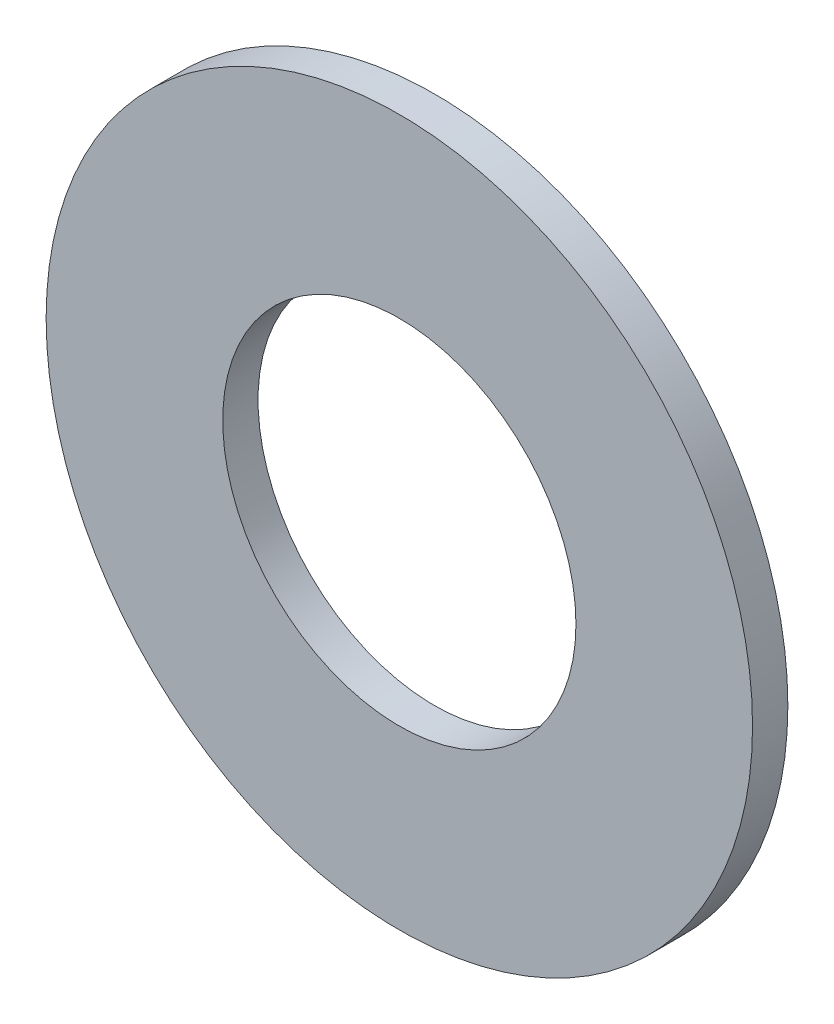
SolidWorks part; units mm, degrees
ref_plane "前视基准面" through (0, 0, 0) normal (0, 0, 1) x (1, 0, 0)
ref_plane "上视基准面" through (0, 0, 0) normal (0, 1, 0) x (1, 0, 0)
ref_plane "右视基准面" through (0, 0, 0) normal (1, 0, 0) x (0, 0, -1)
sketch "草图1" plane through (0, 0, 0) normal (0, 0, 1) x (1, 0, 0)
  circle A0 centre (0, 0) radius 2.5
  circle A1 centre (0, 0) radius 5
  dimension "D1" = 10
  dimension "D2" = 5
extrude "凸台-拉伸1" add sketch "草图1" along normal blind 0.5
